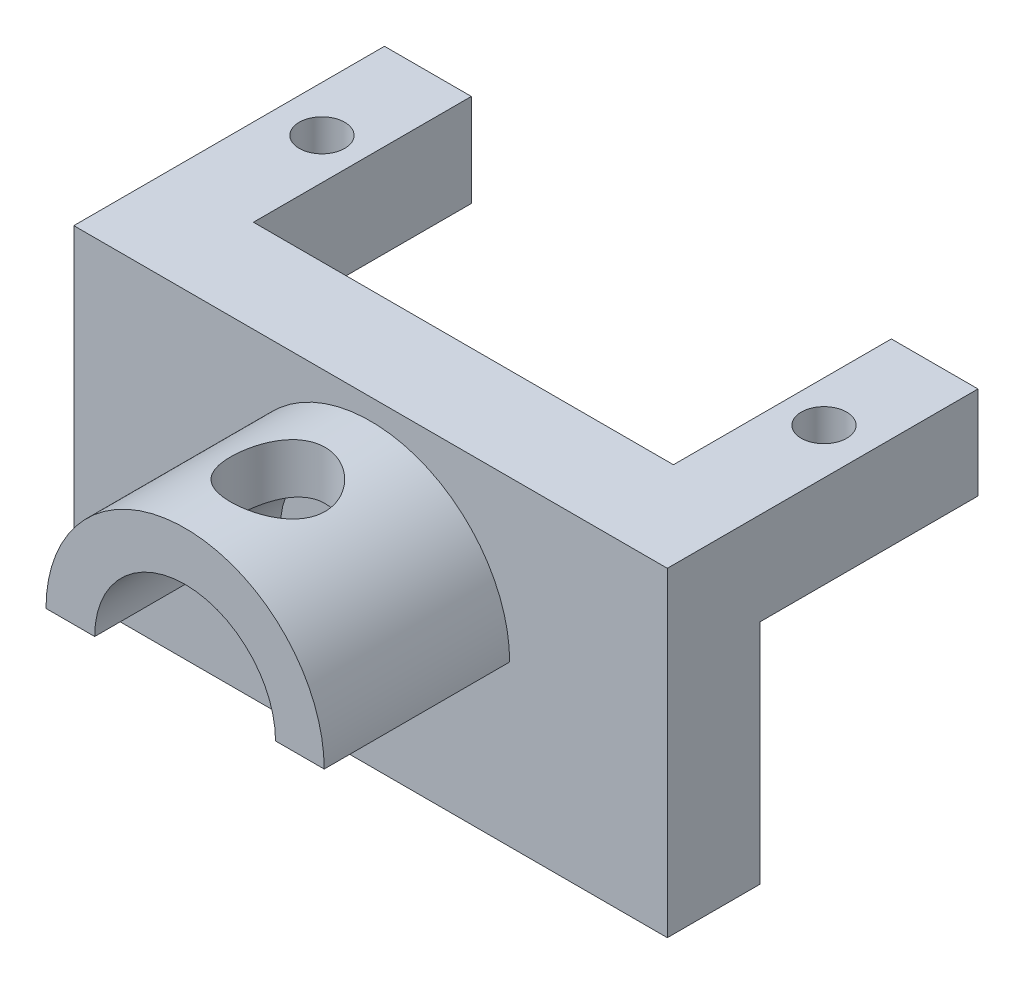
SolidWorks part; units mm, degrees
ref_plane "Front Plane" through (0, 0, 0) normal (0, 0, 1) x (1, 0, 0)
ref_plane "Top Plane" through (0, 0, 0) normal (0, 1, 0) x (1, 0, 0)
ref_plane "Right Plane" through (0, 0, 0) normal (1, 0, 0) x (0, 0, -1)
sketch "Sketch1" plane through (0, 0, 0) normal (0, 0, 1) x (1, 0, 0)
  line L1 (-16.256, -8.763) -> (16.256, -8.763)
  line L2 (-16.256, -8.763) -> (-16.256, 8.763)
  line L3 (-16.256, 8.763) -> (16.256, 8.763)
  line L4 (16.256, -8.763) -> (16.256, 8.763)
  line L5 (-16.256, -8.763) -> (16.256, 8.763) construction
  line L6 (-16.256, 8.763) -> (16.256, -8.763) construction
  point P0 (0, 0)
  dimension "D1" = 32.512
  dimension "D2" = 17.526
extrude "Boss-Extrude1" add sketch "Sketch1" along normal blind 5.08
sketch "Sketch2" plane through (0, 0, 0) normal (0, 0, -1) x (-1, 0, 0)
  line L1 (16.256, 8.763) -> (11.498, 8.763)
  line L2 (16.256, 8.763) -> (16.256, 3.683)
  line L3 (16.256, 3.683) -> (11.498, 3.683)
  line L4 (11.498, 8.763) -> (11.498, 3.683)
  line L5 (-16.256, 8.763) -> (-11.51, 8.763)
  line L6 (-16.256, 8.763) -> (-16.256, 3.683)
  line L7 (-16.256, 3.683) -> (-11.51, 3.683)
  line L8 (-11.51, 8.763) -> (-11.51, 3.683)
  line L10 (-11.256, 8.763) -> (-11.256, -8.737) construction
  line L11 (11.244, 8.763) -> (11.244, -6.737) construction
  point P14 (0, 0)
  dimension "D1" = 5.08
  dimension "D2" = 0.254
  dimension "D3" = 0.254
extrude "Boss-Extrude2" add sketch "Sketch2" along normal blind 11.938
hole_wizard "#40 (0.098) Diameter Hole1" positions "Sketch3" profile "Sketch4" hole size "#40" standard "ANSI Inch" end condition through all
sketch "Sketch3" plane through (0, 8.763, 0) normal (0, 1, 0) x (1, 0, 0)
  point P0 (-13.744, 6)
  point P2 (13.756, 6)
  point P3 (13.756, 6)
  point P6 (13.756, 6)
  point P8 (-13.744, 6)
sketch "Sketch4" plane through (-13.744, 8.763, -6) normal (1, 0, 0) x (0, 0, 1)
  line L0 (0, 0) -> (0, 17.526)
  line L1 (0, 17.526) -> (1.2446, 17.526)
  line L2 (1.2446, 17.526) -> (1.2446, 0)
  line L5 (1.2446, 0) -> (0, 0)
  line L11 (0, -6.35) -> (0, 107.95) construction
  dimension "Thru Hole Dia." = 2.4892
  dimension "Thru Hole Depth" = 17.526
sketch "Sketch5" plane through (0, 0, 5.08) normal (0, 0, 1) x (1, 0, 0)
  line L0 (7.62, 0) -> (4.953, 0)
  line L1 (-4.953, 0) -> (-7.62, 0)
  arc A0 (4.953, 0) -> (-4.953, 0) centre (0, 0) ccw
  arc A1 (7.62, 0) -> (-7.62, 0) centre (0, 0) ccw
  dimension "D1" = 9.906
  dimension "D2" = 15.24
extrude "Boss-Extrude3" add sketch "Sketch5" along normal blind 10.16
ref_plane "Plane4" through (0, 7.62, 0) normal (0, 1, 0) x (1, 0, 0)
sketch "Sketch9" plane through (0, 7.62, 0) normal (0, 1, 0) x (1, 0, 0)
  line L0 (-7.62, -10.16) -> (7.62, -10.16) construction
  line L1 (-7.62, -15.24) -> (-7.62, -5.08) construction
  line L2 (7.62, -15.24) -> (7.62, -5.08) construction
  point P6 (0, -10.16)
hole_wizard "#6 (0.204) Diameter Hole2" positions "Sketch14" profile "Sketch15" hole size "#6" standard "ANSI Inch" end condition through all
sketch "Sketch14" plane through (0, 7.62, 0) normal (0, 1, 0) x (1, 0, 0)
  point P0 (0, -10.16)
sketch "Sketch15" plane through (0, 7.62, 10.16) normal (1, 0, 0) x (0, 0, 1)
  line L0 (0, 0) -> (0, 16.383)
  line L1 (0, 16.383) -> (2.5908, 16.383)
  line L2 (2.5908, 16.383) -> (2.5908, 0)
  line L5 (2.5908, 0) -> (0, 0)
  line L11 (0, -6.35) -> (0, 107.95) construction
  dimension "Thru Hole Dia." = 5.1816
  dimension "Thru Hole Depth" = 16.383
